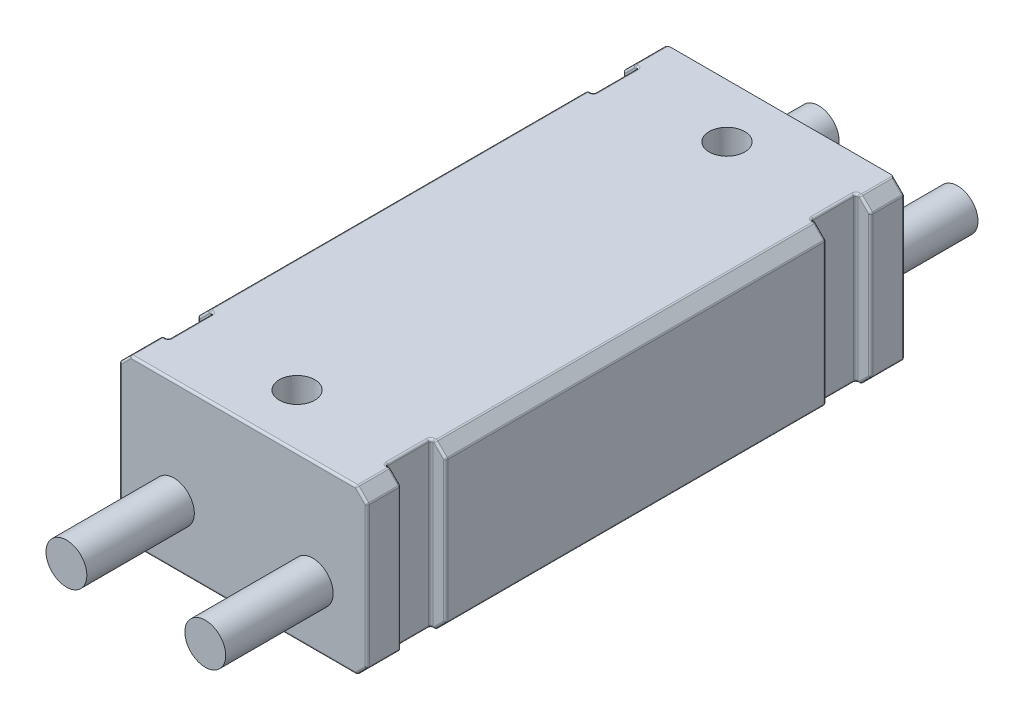
SolidWorks part; units mm, degrees
ref_plane "Front Plane" through (0, 0, 0) normal (0, 0, 1) x (1, 0, 0)
ref_plane "Top Plane" through (0, 0, 0) normal (0, 1, 0) x (1, 0, 0)
ref_plane "Right Plane" through (0, 0, 0) normal (1, 0, 0) x (0, 0, -1)
sketch "Sketch1" plane through (0, 0, 0) normal (0, 1, 0) x (1, 0, 0)
  line L1 (14.6431, -31.75) -> (-14.6431, -31.75)
  line L2 (14.6431, -31.75) -> (14.6431, 31.75)
  line L3 (14.6431, 31.75) -> (-14.6431, 31.75)
  line L4 (-14.6431, -31.75) -> (-14.6431, 31.75)
  line L5 (14.6431, -31.75) -> (-14.6431, 31.75) construction
  line L6 (14.6431, 31.75) -> (-14.6431, -31.75) construction
  point P0 (0, 0)
  dimension "D1" = 63.5
  dimension "D2" = 29.2862
extrude "Boss-Extrude1" add sketch "Sketch1" along normal blind 19.304
sketch "Sketch2" plane through (0, 19.304, 0) normal (0, 1, 0) x (1, 0, 0)
  line L0 (0, -25.4) -> (0, 25.4) construction
  circle A0 centre (0, 25.4) radius 2.1006
  circle A1 centre (0, -25.4) radius 2.1006
  point P4 (0, 0)
  dimension "D2" = 4.2012
  dimension "D1" = 50.8
extrude "Cut-Extrude1" cut sketch "Sketch2" against normal through all
sketch "Sketch3" plane through (0, 0, 31.75) normal (0, 0, 1) x (1, 0, 0)
  line L0 (0, 0) -> (0, 6.9596) construction
  line L1 (5.7912, 6.9596) -> (-5.7912, 6.9596) construction
  line L2 (-8.2042, 4.5466) -> (-8.2042, 0) construction
  line L3 (-14.6431, 0) -> (14.6431, 0) construction
  circle A0 centre (-8.2042, 6.9596) radius 2.413
  circle A1 centre (8.2042, 6.9596) radius 2.413
  point P6 (0, 6.9596)
  dimension "D3" = 4.826
  dimension "D1" = 11.5824
  dimension "D2" = 4.5466
extrude "Boss-Extrude2" add sketch "Sketch3" along normal blind 12.7
sketch "Sketch4" plane through (0, 0, 0) normal (0, 1, 0) x (1, 0, 0)
  line L0 (0, 38.7279) -> (0, -41.6597) construction
  line L1 (14.6431, -31.75) -> (14.6431, 31.75) construction
  line L2 (12.8651, -27.7622) -> (14.6431, -27.7622)
  line L3 (12.8651, -27.7622) -> (12.8651, -22.479)
  line L4 (12.8651, -22.479) -> (14.6431, -22.479)
  line L5 (14.6431, -27.7622) -> (14.6431, -22.479)
  line L6 (12.8651, -27.7622) -> (14.6431, -22.479) construction
  line L7 (12.8651, -22.479) -> (14.6431, -27.7622) construction
  line L8 (-12.8651, -27.7622) -> (-14.6431, -22.479) construction
  line L9 (-12.8651, -22.479) -> (-14.6431, -27.7622) construction
  line L10 (-12.8651, -27.7622) -> (-12.8651, -22.479)
  line L11 (-12.8651, -27.7622) -> (-14.6431, -27.7622)
  line L12 (-14.6431, -27.7622) -> (-14.6431, -22.479)
  line L13 (-12.8651, -22.479) -> (-14.6431, -22.479)
  line L14 (-14.6431, -31.75) -> (14.6431, -31.75) construction
  line L15 (-20.5619, 0) -> (19.6546, 0) construction
  line L16 (-12.8651, 22.479) -> (-14.6431, 27.7622) construction
  line L17 (-12.8651, 27.7622) -> (-14.6431, 22.479) construction
  line L18 (12.8651, 22.479) -> (14.6431, 27.7622) construction
  line L19 (12.8651, 27.7622) -> (14.6431, 22.479) construction
  line L20 (-12.8651, 22.479) -> (-14.6431, 22.479)
  line L21 (-14.6431, 27.7622) -> (-14.6431, 22.479)
  line L22 (-12.8651, 27.7622) -> (-14.6431, 27.7622)
  line L23 (-12.8651, 27.7622) -> (-12.8651, 22.479)
  line L24 (14.6431, 27.7622) -> (14.6431, 22.479)
  line L25 (12.8651, 22.479) -> (14.6431, 22.479)
  line L26 (12.8651, 27.7622) -> (12.8651, 22.479)
  line L27 (12.8651, 27.7622) -> (14.6431, 27.7622)
  point P3 (13.7541, -25.1206)
  point P12 (-13.7541, -25.1206)
  point P27 (-13.7541, 25.1206)
  point P28 (13.7541, 25.1206)
  dimension "D1" = 3.9878
  dimension "D2" = 5.2832
  dimension "D3" = 1.778
extrude "Cut-Extrude4" cut sketch "Sketch4" along normal through all
chamfer "Chamfer1" distance 1.27 angle 45 12 edges at (-14.6431, 0, 0) (14.6431, 0, 0) (-14.6431, 19.304, 0) (14.6431, 19.304, 29.7561) (14.6431, 0, -29.7561) (-14.6431, 0, -29.7561) (-14.6431, 0, 29.7561) (14.6431, 0, 29.7561) (-14.6431, 19.304, 29.7561) (-14.6431, 19.304, -29.7561) (14.6431, 19.304, -29.7561) (14.6431, 19.304, 0)
mirror "Mirror1" about plane through (0, 0, 0) normal (0, 0, 1) of "Boss-Extrude2"
fillet "Fillet1" radius 0.254 94 edges at (-13.1191, 19.304, -27.7622) (-13.1191, 0, -27.7622) (-13.1191, 19.304, 22.479) (-13.1191, 0, 22.479) (-13.1191, 19.304, 27.7622) (-13.1191, 0, 27.7622) (13.1191, 19.304, -22.479) (13.1191, 0, -22.479) (13.1191, 19.304, 27.7622) (13.1191, 0, 27.7622) (13.1191, 19.304, 22.479) (13.1191, 0, 22.479) (13.1191, 19.304, -27.7622) (13.1191, 0, -27.7622) (13.3731, 19.304, -29.7561) (14.0081, 18.669, -31.75) (14.0081, 18.669, -27.7622) (-13.3731, 19.304, -29.7561) (-14.0081, 18.669, -27.7622) (-14.0081, 18.669, -31.75) (-14.0081, 0.635, -27.7622) (-13.3731, 0, -29.7561) (-14.0081, 0.635, -31.75) (-14.6431, 18.034, -29.7561) (-14.6431, 9.652, -27.7622) (-14.6431, 1.27, -29.7561) (-14.6431, 9.652, -31.75) (-13.1191, 19.304, -22.479) (-13.1191, 0, -22.479) (-12.8651, 9.652, -27.7622) (-12.8651, 19.304, -25.1206) (-12.8651, 9.652, -22.479) (-12.8651, 0, -25.1206) (-14.0081, 0.635, 22.479) (-13.3731, 0, 0) (-14.0081, 0.635, -22.479) (-14.6431, 9.652, 22.479) (-14.6431, 1.27, 0) (-14.6431, 9.652, -22.479) (-13.3731, 19.304, 0) (-14.0081, 18.669, 22.479) (-14.6431, 18.034, 0) (-14.0081, 18.669, -22.479) (-13.3731, 19.304, 29.7561) (-14.0081, 18.669, 31.75) (-14.0081, 18.669, 27.7622) (-12.8651, 9.652, 22.479) (-12.8651, 19.304, 25.1206) (-12.8651, 9.652, 27.7622) (-12.8651, 0, 25.1206) (-14.6431, 18.034, 29.7561) (-14.6431, 9.652, 31.75) (-14.6431, 9.652, 27.7622) (-14.6431, 1.27, 29.7561) (-14.0081, 0.635, 31.75) (-13.3731, 0, 29.7561) (-14.0081, 0.635, 27.7622) (14.0081, 0.635, 27.7622) (13.3731, 0, 29.7561) (14.0081, 0.635, 31.75) (14.0081, 0.635, -22.479) (13.3731, 0, 0) (14.0081, 0.635, 22.479) (14.0081, 0.635, -31.75) (13.3731, 0, -29.7561) (14.0081, 0.635, -27.7622) (13.3731, 19.304, 0) (14.0081, 18.669, -22.479) (14.0081, 18.669, 22.479) (14.6431, 18.034, -29.7561) (14.6431, 9.652, -31.75) (14.6431, 1.27, -29.7561) (14.6431, 9.652, -27.7622) (12.8651, 9.652, -22.479) (12.8651, 19.304, -25.1206) (12.8651, 9.652, -27.7622) (12.8651, 0, -25.1206) (14.6431, 1.27, 0) (14.6431, 9.652, 22.479) (14.6431, 18.034, 0) (14.6431, 9.652, -22.479) (14.6431, 18.034, 29.7561) (14.6431, 9.652, 27.7622) (14.6431, 1.27, 29.7561) (14.6431, 9.652, 31.75) (12.8651, 9.652, 27.7622) (12.8651, 19.304, 25.1206) (12.8651, 9.652, 22.479) (12.8651, 0, 25.1206) (0, 0, 31.75) (0, 19.304, 31.75) (13.3731, 19.304, 29.7561) (14.0081, 18.669, 27.7622) (14.0081, 18.669, 31.75)
